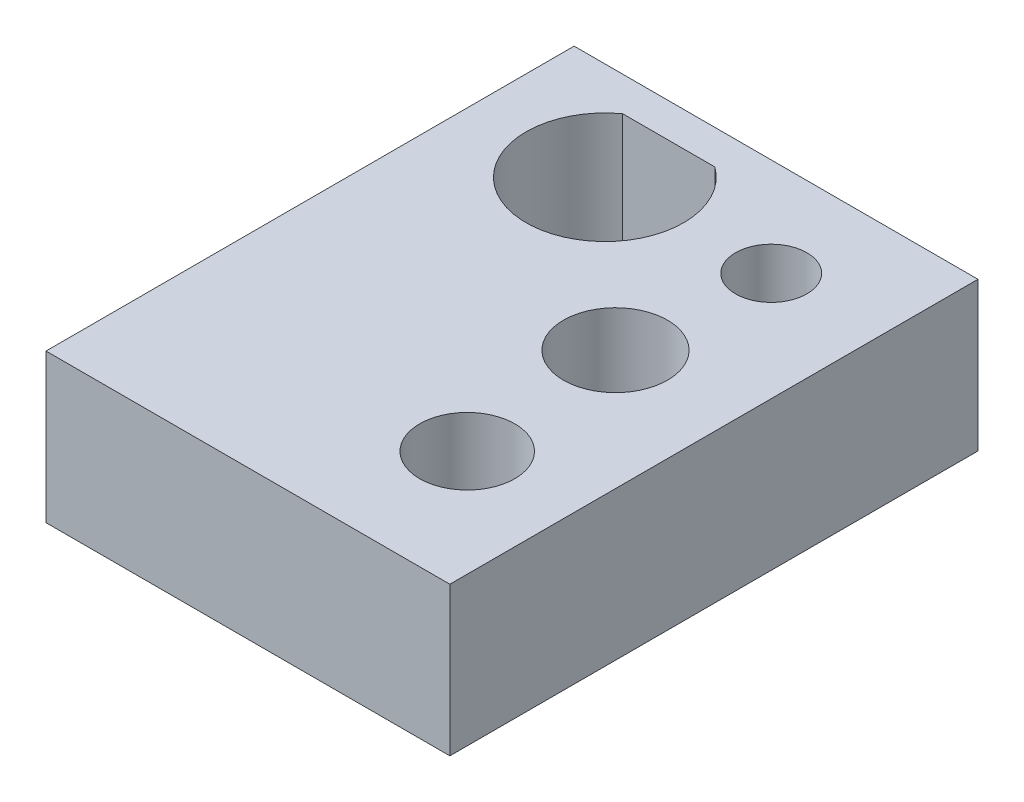
SolidWorks part; units mm, degrees
ref_plane "Front Plane" through (0, 0, 0) normal (0, 0, 1) x (1, 0, 0)
ref_plane "Top Plane" through (0, 0, 0) normal (0, 1, 0) x (1, 0, 0)
ref_plane "Right Plane" through (0, 0, 0) normal (1, 0, 0) x (0, 0, -1)
sketch "Sketch1" plane through (0, 0, 0) normal (0, 1, 0) x (1, 0, 0)
  line L1 (-12.5978, 4.5405) -> (0.9842, 4.5405)
  line L2 (-12.5978, 4.5405) -> (-12.5978, -13.2205)
  line L3 (-12.5978, -13.2205) -> (0.9842, -13.2205)
  line L4 (0.9842, 4.5405) -> (0.9842, -13.2205)
  line L5 (-9.8109, 3.3878) -> (-6.7125, 3.3878)
  arc A0 (-9.8109, 3.3878) -> (-6.7125, 3.3878) centre (-8.2617, 1.2378) ccw
  circle A3 centre (-2.5961, -9.0561) radius 1.6
  circle A4 centre (-2.667, 1.2378) radius 1.2
  circle A5 centre (-3.0467, -3.6196) radius 1.75
  dimension "D1" = 5.3
  dimension "D2" = 2.15
  dimension "D5" = 3.2
  dimension "D6" = 2.4
  dimension "D7" = 3.5
sketch "Sketch2" plane through (0, 0, 0) normal (0, 1, 0) x (1, 0, 0)
extrude "Boss-Extrude1" add sketch "Sketch1" along normal blind 5
